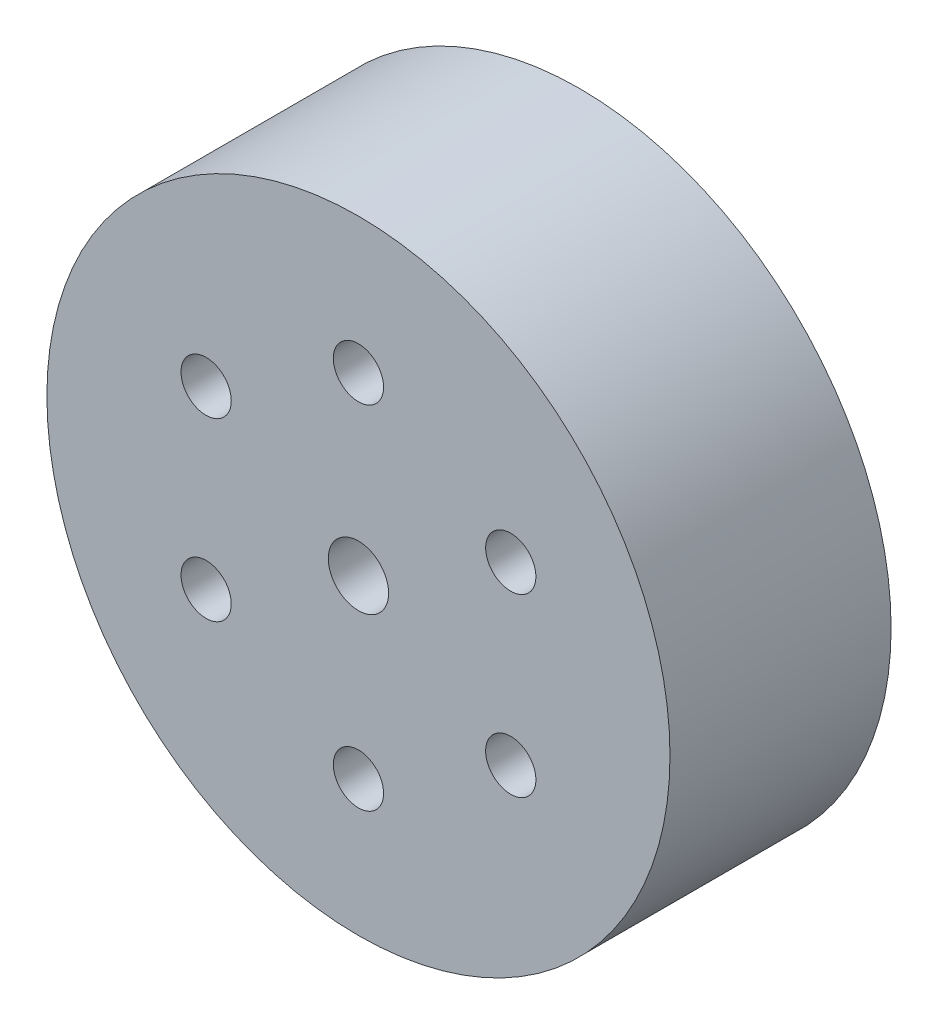
SolidWorks part; units mm, degrees
ref_plane "Front" through (0, 0, 0) normal (0, 0, 1) x (1, 0, 0)
ref_plane "Top" through (0, 0, 0) normal (0, 1, 0) x (1, 0, 0)
ref_plane "Right" through (0, 0, 0) normal (1, 0, 0) x (0, 0, -1)
sketch "Esquisse1" plane through (0, 0, 0) normal (0, 0, 1) x (1, 0, 0)
  line L0 (0, 0) -> (0, 8.75) construction
  circle A0 centre (0, 0) radius 15.5
  circle A1 centre (0, 0) radius 1.5
  circle A2 centre (0, 8.75) radius 1.25
  circle A3 centre (7.5777, 4.375) radius 1.25
  circle A4 centre (7.5777, -4.375) radius 1.25
  circle A5 centre (0, -8.75) radius 1.25
  circle A6 centre (-7.5777, -4.375) radius 1.25
  circle A7 centre (-7.5777, 4.375) radius 1.25
  point P6 (0, 0)
  point P7 (-9.3948, 7.6653)
  point P18 (0, 0)
  point P19 (0, 0)
  dimension "D1" = 3
  dimension "D2" = 31
  dimension "D3" = 2.5
  dimension "D4" = 8.75
  dimension "D5" = 6
extrude "Boss.-Extru.1" add sketch "Esquisse1" along normal blind 11
